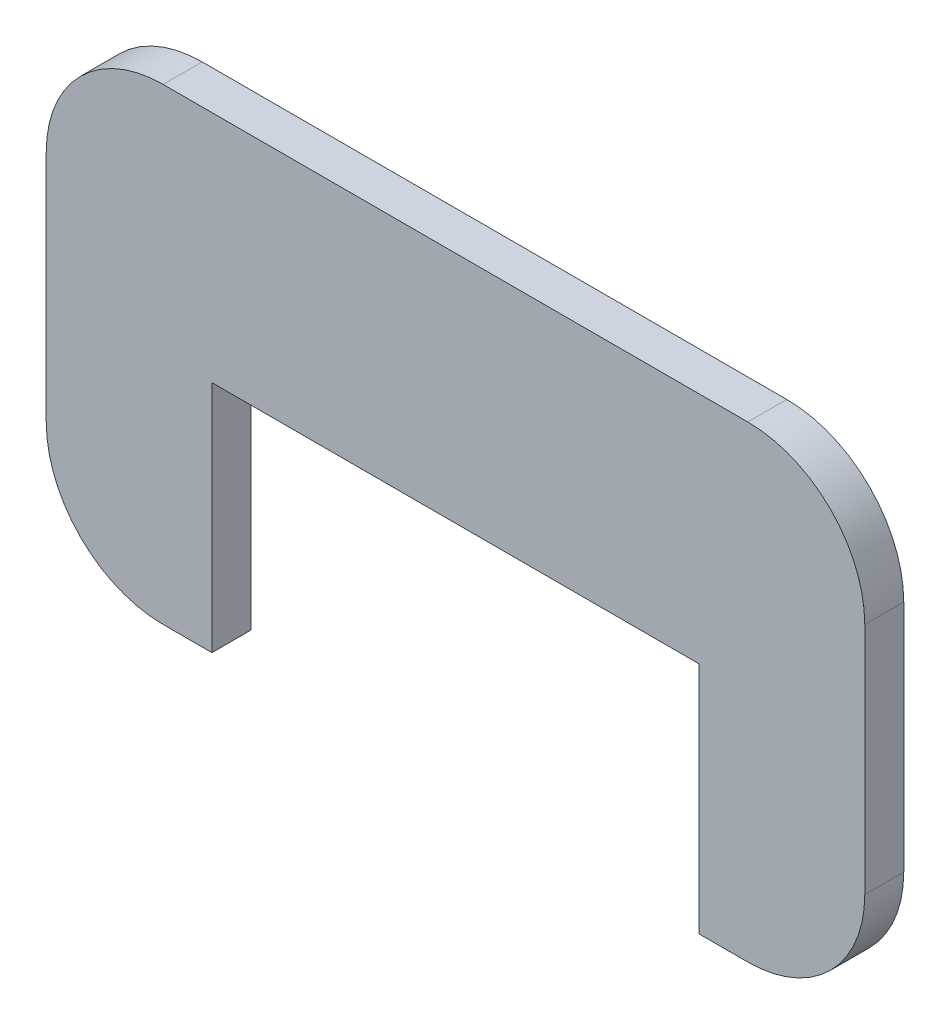
SolidWorks part; units mm, degrees
ref_plane "Front Plane" through (0, 0, 0) normal (0, 0, 1) x (1, 0, 0)
ref_plane "Top Plane" through (0, 0, 0) normal (0, 1, 0) x (1, 0, 0)
ref_plane "Right Plane" through (0, 0, 0) normal (1, 0, 0) x (0, 0, -1)
sketch "Sketch1" plane through (0, 0, 0) normal (0, 0, 1) x (1, 0, 0)
  line L0 (-2, -2) -> (19, -2)
  line L1 (0, 0) -> (17, 0)
  line L2 (0, 0) -> (0, 8)
  line L3 (0, 8) -> (17, 8)
  line L4 (17, 0) -> (17, 8)
  line L5 (19, -2) -> (19, 10)
  line L6 (-2, 10) -> (19, 10)
  line L7 (-2, -2) -> (-2, 10)
  line L8 (1, 7) -> (16, 7)
  line L9 (16, 1) -> (16, 7)
  line L10 (1, 1) -> (16, 1)
  line L11 (1, 1) -> (1, 7)
  line L12 (8.5, 10) -> (8.5, -2) construction
  line L14 (2.25, -2) -> (14.75, -2)
  line L15 (2.25, -2) -> (2.25, 4)
  line L16 (2.25, 4) -> (14.75, 4)
  line L17 (14.75, -2) -> (14.75, 4)
  dimension "D1" = 17
  dimension "D2" = 8
  dimension "D3" = 2
  dimension "D5" = 12.5
  dimension "D6" = 6
  dimension "D7" = 0
  dimension "D8" = 6.25
  dimension "D4" = 1
extrude "Boss-Extrude1" add sketch "Sketch1" along normal blind 1 contours L6 L12 L3 L4 L1 L17 L0 L5 | L12 L6 L7 L0 L15 L1 L2 L3 | L12 L3 L2 L1 L15 L10 L11 L8 | L12 L8 L11 L10 L15 L16 | L8 L12 L16 L17 L10 L9 | L3 L12 L8 L9 L10 L17 L1 L4
fillet "Fillet2" radius 3 4 edges at (-2, -2, 0.5) (19, -2, 0.5) (19, 10, 0.5) (-2, 10, 0.5)
